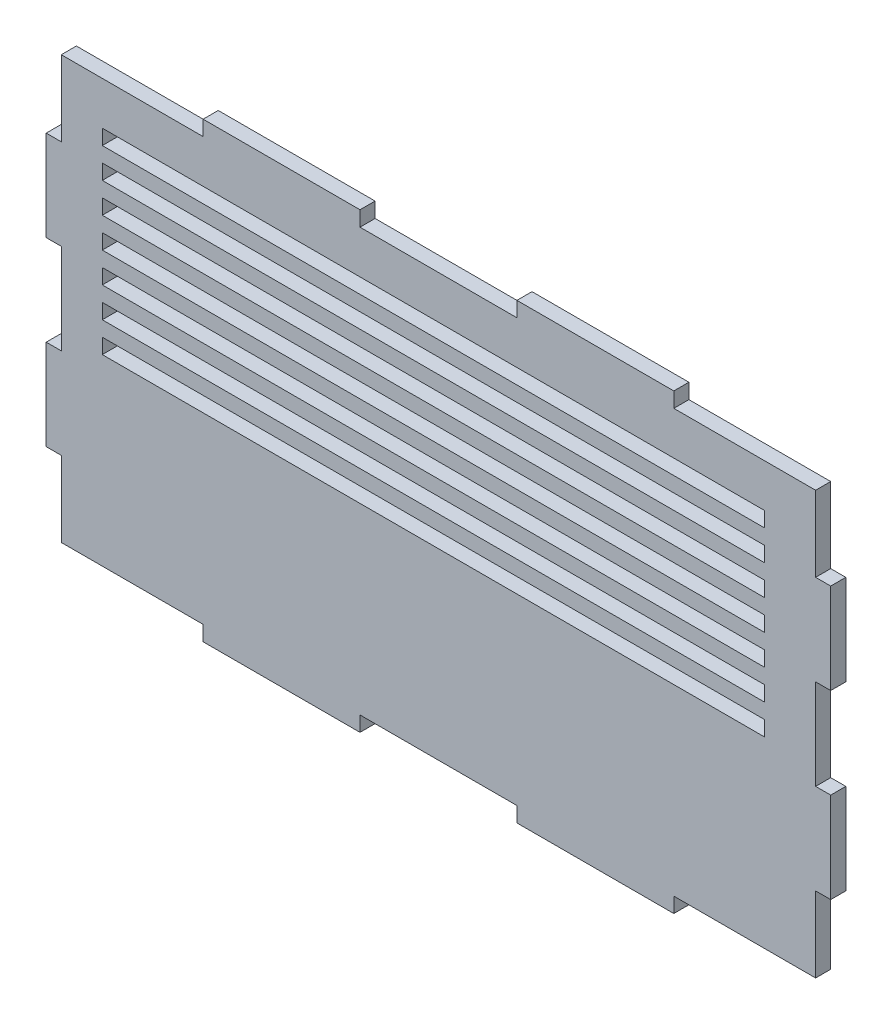
SolidWorks part; units mm, degrees
ref_plane "Alzado" through (0, 0, 0) normal (0, 0, 1) x (1, 0, 0)
ref_plane "Planta" through (0, 0, 0) normal (0, 1, 0) x (1, 0, 0)
ref_plane "Vista lateral" through (0, 0, 0) normal (1, 0, 0) x (0, 0, -1)
sketch "Croquis1" plane through (0, 0, 0) normal (0, 0, 1) x (1, 0, 0)
  line L0 (130, 150) -> (130, 129.9372) construction
  line L1 (52, 0) -> (104, 0)
  line L2 (0, 30) -> (0, 60)
  line L3 (52, 150) -> (104, 150)
  line L4 (260, 30) -> (260, 60)
  line L5 (0, 75) -> (16.5526, 75) construction
  line L6 (0, 120) -> (5, 120)
  line L7 (0, 90) -> (0, 120)
  line L8 (5, 90) -> (0, 90)
  line L9 (0, 30) -> (5, 30)
  line L10 (0, 0) -> (5, 0) construction
  line L11 (5, 60) -> (0, 60)
  line L12 (5, 30) -> (5, 5)
  line L13 (5, 60) -> (5, 90)
  line L14 (5, 120) -> (5, 145)
  line L15 (0, 30) -> (0, 0) construction
  line L16 (255, 30) -> (255, 5)
  line L17 (260, 30) -> (255, 30)
  line L18 (255, 60) -> (260, 60)
  line L19 (255, 60) -> (255, 90)
  line L20 (255, 90) -> (260, 90)
  line L21 (260, 120) -> (255, 120)
  line L22 (255, 120) -> (255, 145)
  line L23 (260, 90) -> (260, 120)
  line L24 (52, 150) -> (52, 145)
  line L25 (208, 5) -> (255, 5)
  line L26 (104, 145) -> (104, 150)
  line L27 (208, 150) -> (208, 145)
  line L28 (156, 145) -> (156, 150)
  line L29 (208, 0) -> (208, 5)
  line L30 (52, 145) -> (5, 145)
  line L31 (104, 145) -> (156, 145)
  line L32 (208, 145) -> (255, 145)
  line L33 (156, 150) -> (208, 150)
  line L34 (156, 5) -> (156, 0)
  line L35 (104, 5) -> (156, 5)
  line L36 (104, 5) -> (104, 0)
  line L37 (52, 0) -> (52, 5)
  line L38 (52, 5) -> (5, 5)
  line L39 (156, 0) -> (208, 0)
  line L40 (0, 0) -> (52, 0) construction
  line L42 (245, 135) -> (10, 135) construction
  line L43 (245, 135) -> (245, 15) construction
  line L44 (245, 15) -> (10, 15) construction
  line L45 (10, 135) -> (10, 15) construction
  line L46 (237.9932, 130.7179) -> (18.5825, 130.7179)
  line L47 (237.9932, 130.7179) -> (237.9932, 125.7179)
  line L70 (18.5825, 130.7179) -> (18.5825, 125.7179)
  line L71 (237.9932, 125.7179) -> (18.5825, 125.7179)
  line L157 (237.9932, 120.7179) -> (18.5825, 120.7179)
  line L159 (237.9932, 115.7179) -> (18.5825, 115.7179)
  line L161 (237.9932, 120.7179) -> (237.9932, 115.7179)
  line L163 (18.5825, 120.7179) -> (18.5825, 115.7179)
  line L165 (237.9932, 110.7179) -> (18.5825, 110.7179)
  line L167 (237.9932, 105.7179) -> (18.5825, 105.7179)
  line L169 (237.9932, 110.7179) -> (237.9932, 105.7179)
  line L171 (18.5825, 110.7179) -> (18.5825, 105.7179)
  line L173 (237.9932, 100.7179) -> (18.5825, 100.7179)
  line L176 (237.9932, 95.7179) -> (18.5825, 95.7179)
  line L178 (237.9932, 100.7179) -> (237.9932, 95.7179)
  line L180 (18.5825, 100.7179) -> (18.5825, 95.7179)
  line L181 (237.9932, 90.7179) -> (18.5825, 90.7179)
  line L184 (237.9932, 85.7179) -> (18.5825, 85.7179)
  line L185 (237.9932, 90.7179) -> (237.9932, 85.7179)
  line L186 (18.5825, 90.7179) -> (18.5825, 85.7179)
  line L187 (237.9932, 80.7179) -> (18.5825, 80.7179)
  line L188 (237.9932, 75.7179) -> (18.5825, 75.7179)
  line L189 (237.9932, 80.7179) -> (237.9932, 75.7179)
  line L190 (18.5825, 80.7179) -> (18.5825, 75.7179)
  line L191 (237.9932, 70.7179) -> (18.5825, 70.7179)
  line L192 (237.9932, 65.7179) -> (18.5825, 65.7179)
  line L193 (237.9932, 70.7179) -> (237.9932, 65.7179)
  line L194 (18.5825, 70.7179) -> (18.5825, 65.7179)
  dimension "D1" = 5
  dimension "D2" = 260
  dimension "D3" = 5
  dimension "D4" = 30
  dimension "D5" = 30
  dimension "D6" = 52
  dimension "D7" = 52
  dimension "D8" = 5
  dimension "D9" = 150
  dimension "D10" = 52
  dimension "D11" = 25
  dimension "D12" = 10
  dimension "D13" = 10
  dimension "D14" = 10
  dimension "D15" = 235
  dimension "D16" = 5
  dimension "D17" = 7
extrude "Saliente-Extruir1" add sketch "Croquis1" along normal blind 5
